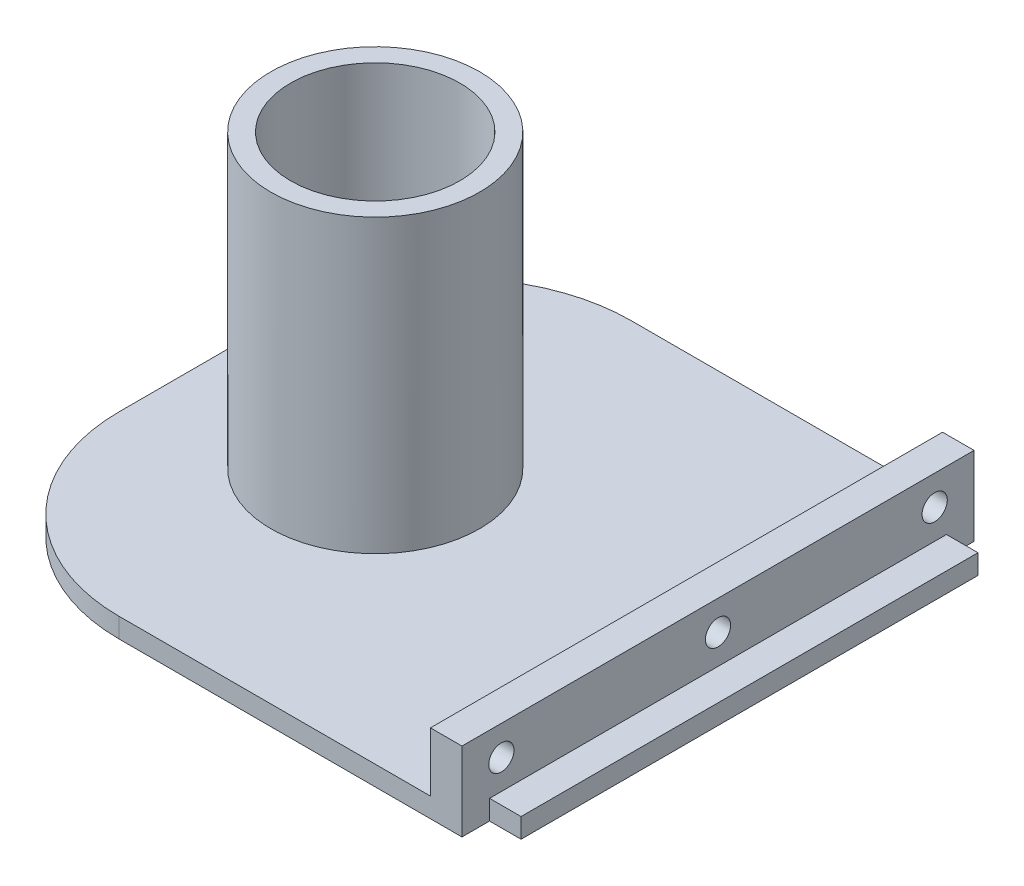
SolidWorks part; units mm, degrees
ref_plane "Front Plane" through (0, 0, 0) normal (0, 0, 1) x (1, 0, 0)
ref_plane "Top Plane" through (0, 0, 0) normal (0, 1, 0) x (1, 0, 0)
ref_plane "Right Plane" through (0, 0, 0) normal (1, 0, 0) x (0, 0, -1)
sketch "Sketch1" plane through (0, 0, 0) normal (0, 1, 0) x (1, 0, 0)
  line L0 (31, 32.5) -> (31, 29)
  line L1 (-12.51, 32.5) -> (31, 32.5)
  line L2 (-35, 10.01) -> (-35, -10.01)
  line L3 (-12.51, -32.5) -> (31, -32.5)
  line L4 (35, 29) -> (35, -29)
  line L5 (-35, 32.5) -> (31, -28.7857) construction
  line L6 (-35, -32.5) -> (31, 28.7857) construction
  line L7 (31, 29) -> (35, 29)
  line L9 (31, -29) -> (35, -29)
  line L10 (31, -32.5) -> (31, -29)
  line L11 (35, 32.5) -> (35, 29) construction
  line L12 (31, 28.7857) -> (35, 32.5) construction
  line L13 (31, 32.5) -> (35, 32.5) construction
  line L14 (35, -29) -> (35, -32.5) construction
  line L15 (31, -28.7857) -> (35, -32.5) construction
  line L16 (31, -32.5) -> (35, -32.5) construction
  line L17 (31, -31.6753) -> (31, -32.5) construction
  arc A0 (-12.51, -32.5) -> (-35, -10.01) centre (-12.51, -10.01) cw
  arc A1 (-35, 10.01) -> (-12.51, 32.5) centre (-12.51, 10.01) cw
  point P0 (0, 0)
  point P14 (35, 0)
  dimension "D3" = 22.49
  dimension "D1" = 70
  dimension "D2" = 65
  dimension "D4" = 58
  dimension "D5" = 4
extrude "Boss-Extrude1" add sketch "Sketch1" along normal mid plane 2.5
sketch "Sketch3" plane through (0, 1.25, 0) normal (0, 1, 0) x (1, 0, 0)
  line L0 (0, 0) -> (-43.6509, 0) construction
  line L1 (-12.51, 32.5) -> (-12.51, -32.5) construction
  circle A0 centre (-12.51, 0) radius 13.25
  circle A1 centre (-12.51, 0) radius 10.75
  dimension "D1" = 26.5
  dimension "D2" = 21.5
extrude "Boss-Extrude2" add sketch "Sketch3" along normal blind 37
sketch "Sketch4" plane through (0, 1.25, 0) normal (0, 1, 0) x (1, 0, 0)
  line L0 (31, 32.5) -> (31, -32.5) construction
  line L3 (35, -29) -> (35, 29) construction
  line L4 (31, 32.5) -> (31, -32.5)
  line L5 (31, -32.5) -> (27, -32.5)
  line L6 (27, -32.5) -> (27, 32.5)
  line L7 (27, 32.5) -> (31, 32.5)
  line L8 (0, 0) -> (26.2112, 0) construction
  line L10 (31, 32.5) -> (-12.51, 32.5) construction
  dimension "D1" = 4
  dimension "D2" = 4
extrude "Boss-Extrude3" add sketch "Sketch4" along normal blind 7.5
sketch "Sketch5" plane through (27, 0, 0) normal (-1, 0, 0) x (0, 0, 1)
  line L0 (0, 0) -> (0, 16.1534) construction
  line L1 (-32.5, 8.75) -> (-32.5, 1.25) construction
  circle A0 centre (-27.5, 5) radius 1.6
  circle A1 centre (0, 5) radius 1.6
  circle A2 centre (27.5, 5) radius 1.6
  point P7 (-32.5, 5)
  dimension "D1" = 3.2
  dimension "D3" = 3.2
  dimension "D2" = 5
extrude "Cut-Extrude1" cut sketch "Sketch5" against normal blind 7.5
chamfer "Chamfer1" distance 1.5 angle 45 3 edges at (27, 5, 25.9) (27, 5, 1.6) (27, 5, -25.9)
